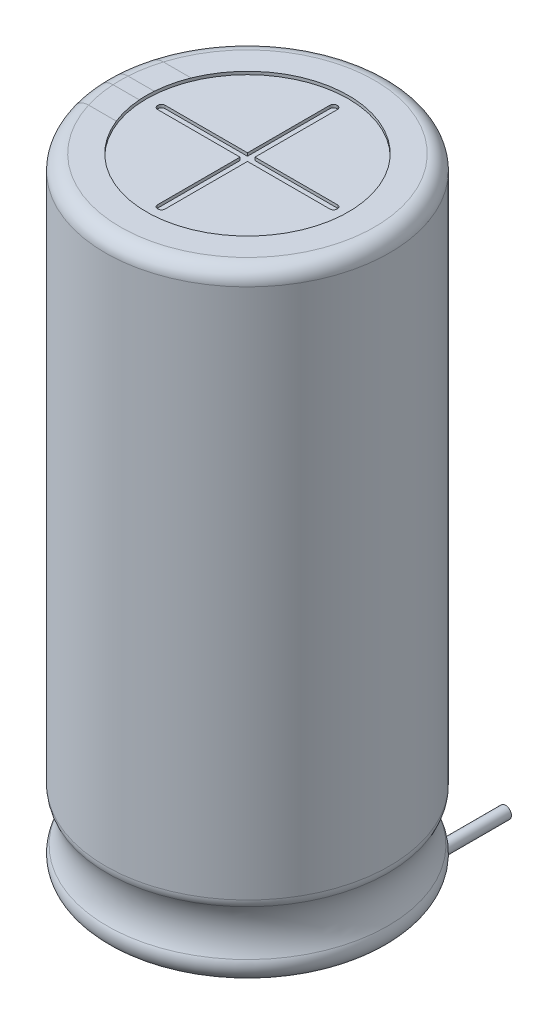
SolidWorks part; units mm, degrees
ref_plane "Front" through (0, 0, 0) normal (0, 0, 1) x (1, 0, 0)
ref_plane "Top" through (0, 0, 0) normal (0, 1, 0) x (1, 0, 0)
ref_plane "Right" through (0, 0, 0) normal (1, 0, 0) x (0, 0, -1)
sketch "Эскиз2" plane through (0, 0, 0) normal (0, 0, 1) x (1, 0, 0)
  line L0 (0, 0) -> (8.5, 0)
  line L1 (9.5, 5) -> (9.5, 40.5)
  line L2 (8.5, 41.5) -> (0, 41.5)
  line L3 (0, 0) -> (0, 41.5) construction
  line L4 (0, 0) -> (0, 41.5)
  arc A0 (8.5, 0) -> (9.5, 1) centre (8.5, 1) ccw
  arc A1 (9.5, 40.5) -> (8.5, 41.5) centre (8.5, 40.5) ccw
  arc A2 (9.5, 1) -> (9.3824, 1.4706) centre (8.5, 1) ccw
  arc A3 (9.3824, 4.5294) -> (9.3824, 1.4706) centre (12.25, 3) ccw
  arc A4 (9.3824, 4.5294) -> (9.5, 5) centre (8.5, 5) ccw
  point P7 (9.5, 0)
  point P10 (9.5, 41.5)
  point P12 (8.7044, 2.0685)
  point P14 (9.4697, 1)
  point P15 (9.3255, 1.5645)
  point P18 (9.3375, 2.243)
  point P19 (9.1788, 2.1839)
  point P20 (9.2951, 1.5645)
  point P21 (0, 0)
  point P22 (9.5, 2.9949)
  point P24 (9.3022, 3.1694)
  point P25 (9.3284, 2.2287)
  point P26 (0, 0)
  point P27 (9.0616, 3.6498)
  point P29 (0, 0)
  point P30 (0, 0)
  point P31 (9, 3)
  dimension "D3" = 1
  dimension "D4" = 0.5
  dimension "D1" = 9.5
  dimension "D2" = 41.5
  dimension "D5" = 4
revolve "Повернуть1" add sketch "Эскиз2" angle 360 about L3
sketch "Эскиз3" plane through (0, 41.5, 0) normal (0, 1, 0) x (1, 0, 0)
  circle A0 centre (0, 0) radius 6.75
  dimension "D1" = 13.5
extrude "Вырез-Вытянуть1" cut sketch "Эскиз3" against normal blind 0.2
sketch "Эскиз4" plane through (0, 41.3, 0) normal (0, 1, 0) x (1, 0, 0)
  line L0 (-0.25, -0.25) -> (-0.25, -5.76)
  line L1 (-0.01, 6) -> (0.01, 6)
  line L2 (-0.25, 5.76) -> (-0.25, 0.25)
  line L3 (-0.01, -6) -> (0.01, -6)
  line L4 (0.25, 5.76) -> (0.25, 0.25)
  line L5 (-5.76, 0.25) -> (-0.25, 0.25)
  line L6 (-6, 0.01) -> (-6, -0.01)
  line L7 (-5.76, -0.25) -> (-0.25, -0.25)
  line L8 (6, 0.01) -> (6, -0.01)
  line L9 (0.25, 0.25) -> (5.76, 0.25)
  line L10 (0.25, -0.25) -> (0.25, -5.76)
  line L11 (0.25, -0.25) -> (5.76, -0.25)
  arc A0 (0.01, 6) -> (0.25, 5.76) centre (0.01, 5.76) cw
  arc A1 (-0.01, 6) -> (-0.25, 5.76) centre (-0.01, 5.76) ccw
  arc A2 (5.76, -0.25) -> (6, -0.01) centre (5.76, -0.01) ccw
  arc A3 (5.76, 0.25) -> (6, 0.01) centre (5.76, 0.01) cw
  arc A4 (0.01, -6) -> (0.25, -5.76) centre (0.01, -5.76) ccw
  arc A5 (-0.25, -5.76) -> (-0.01, -6) centre (-0.01, -5.76) ccw
  arc A6 (-6, -0.01) -> (-5.76, -0.25) centre (-5.76, -0.01) ccw
  arc A7 (-5.76, 0.25) -> (-6, 0.01) centre (-5.76, 0.01) ccw
  point P15 (0.25, 6)
  point P18 (-0.25, 6)
  point P23 (6, 0.25)
  point P26 (0.25, -6)
  point P31 (-6, -0.25)
  point P34 (-6, 0.25)
  dimension "D9" = 0.24
  dimension "D1" = 0.5
  dimension "D2" = 0.5
  dimension "D3" = 0.25
  dimension "D4" = 0.25
  dimension "D5" = 12
  dimension "D6" = 6
  dimension "D7" = 12
  dimension "D8" = 6
extrude "Вырез-Вытянуть2" cut sketch "Эскиз4" against normal blind 0.2
sketch "Эскиз5" plane through (0, 0, 0) normal (0, -1, 0) x (1, 0, 0)
  circle A0 centre (0, 0) radius 7.3
  dimension "D1" = 14.6
extrude "Вырез-Вытянуть3" cut sketch "Эскиз5" against normal blind 0.2
sketch "Эскиз6" plane through (0, 0.2, 0) normal (0, -1, 0) x (1, 0, 0)
  line L1 (-5.3376, 2) -> (5.3376, 2)
  line L3 (-5.3376, -2) -> (5.3376, -2)
  arc A0 (-5.3376, -2) -> (5.3376, -2) centre (0, 0) ccw
  arc A1 (5.3376, 2) -> (-5.3376, 2) centre (0, 0) ccw
  dimension "D1" = 11.4
  dimension "D2" = 4
  dimension "D3" = 2
extrude "Бобышка-Вытянуть1" add sketch "Эскиз6" along normal blind 1.2
sketch "Эскиз9" plane through (0, 0, 0) normal (1, 0, 0) x (0, 0, -1)
  line L1 (-2.5, 45) -> (2.5, 45)
  line L2 (-2.5, 45) -> (-2.5, -5)
  line L3 (-2.5, -5) -> (2.5, -5)
  line L4 (2.5, 45) -> (2.5, -5)
  line L5 (-0.5, 39) -> (-0.5, 36)
  line L6 (-0.5, 44) -> (0.5, 44)
  line L7 (-0.5, 44) -> (-0.5, 41)
  line L8 (-0.5, 41) -> (0.5, 41)
  line L9 (0.5, 44) -> (0.5, 41)
  line L10 (-0.5, 39) -> (0.5, 39)
  line L11 (0.5, 39) -> (0.5, 36)
  line L12 (-0.5, 36) -> (0.5, 36)
  line L13 (-0.5, 34) -> (-0.5, 31)
  line L14 (-0.5, 34) -> (0.5, 34)
  line L15 (0.5, 34) -> (0.5, 31)
  line L16 (-0.5, 31) -> (0.5, 31)
  line L17 (-0.5, 29) -> (-0.5, 26)
  line L18 (-0.5, 29) -> (0.5, 29)
  line L19 (0.5, 29) -> (0.5, 26)
  line L20 (-0.5, 26) -> (0.5, 26)
  line L21 (-0.5, 24) -> (-0.5, 21)
  line L22 (-0.5, 24) -> (0.5, 24)
  line L23 (0.5, 24) -> (0.5, 21)
  line L24 (-0.5, 21) -> (0.5, 21)
  line L25 (-0.5, 19) -> (-0.5, 16)
  line L26 (-0.5, 19) -> (0.5, 19)
  line L27 (0.5, 19) -> (0.5, 16)
  line L28 (-0.5, 16) -> (0.5, 16)
  line L29 (-0.5, 14) -> (-0.5, 11)
  line L30 (-0.5, 14) -> (0.5, 14)
  line L31 (0.5, 14) -> (0.5, 11)
  line L32 (-0.5, 11) -> (0.5, 11)
  line L33 (-0.5, 9) -> (-0.5, 6)
  line L34 (-0.5, 9) -> (0.5, 9)
  line L35 (0.5, 9) -> (0.5, 6)
  line L36 (-0.5, 6) -> (0.5, 6)
  line L37 (-0.5, 4) -> (-0.5, 1)
  line L38 (-0.5, 4) -> (0.5, 4)
  line L39 (0.5, 4) -> (0.5, 1)
  line L40 (-0.5, 1) -> (0.5, 1)
  line L41 (-0.5, -1) -> (-0.5, -4)
  line L42 (-0.5, -1) -> (0.5, -1)
  line L43 (0.5, -1) -> (0.5, -4)
  line L44 (-0.5, -4) -> (0.5, -4)
  line L45 (2, -1) -> (5.7, -1) construction
  point P11 (0, 44)
  point P12 (0, 45)
  dimension "D1" = 5
  dimension "D2" = 2.5
  dimension "D3" = 50
  dimension "D4" = 3
  dimension "D5" = 1
  dimension "D6" = 1
  dimension "D8" = 5
  dimension "D9" = 4
  dimension "D7" = 10
split line "Разделяющая линия5"
sketch "Эскиз7" plane through (0, 0.2, 0) normal (0, -1, 0) x (1, 0, 0)
  circle A0 centre (-3.75, 0) radius 0.4
  circle A1 centre (3.75, 0) radius 0.4
  point P4 (0, 0)
  dimension "D1" = 0.8
  dimension "D2" = 0.8
  dimension "D3" = 7.5
  dimension "D4" = 3.75
extrude "Бобышка-Вытянуть2" [suppressed] add sketch "Эскиз7" along normal blind 5.2
ref_plane "Плоскость2" through (-3.75, 0, 0) normal (1, 0, 0) x (0, 0, -1)
sketch "Эскиз10" plane through (-3.75, 0, 0) normal (1, 0, 0) x (0, 0, -1)
  line L0 (0, 0.2) -> (0, 0)
  line L1 (1.5, -1.5) -> (13.5, -1.5)
  line L2 (9.5, 5) -> (9.5, 40.5) construction
  line L3 (-7.3, 0.2) -> (7.3, 0.2) construction
  line L5 (2, -1) -> (5.7, -1) construction
  arc A0 (0, 0) -> (1.5, -1.5) centre (1.5, 0) ccw
  point P2 (0, 0)
  point P4 (0, 0)
  point P7 (-1.122, 0.2)
  point P12 (5.0868, -5.5799)
  point P15 (0, -1.5)
  dimension "D4" = 1.5
  dimension "D1" = 9.5
  dimension "D2" = 4
  dimension "D3" = 0.5
ref_plane "Плоскость3" through (-3.75, -1.5, -13.5) normal (0, 0, -1) x (-1, 0, 0)
sketch "Эскиз11" plane through (-3.75, -1.5, -13.5) normal (0, 0, -1) x (-1, 0, 0)
  circle A0 centre (0, 0) radius 0.4
  dimension "D1" = 0.8
sweep "По траектории3" add profiles "Эскиз11" path "Эскиз10"
pattern_linear "Линейный массив1" count 2 spacing 7.5 along (1, 0, 0) of "По траектории3"
